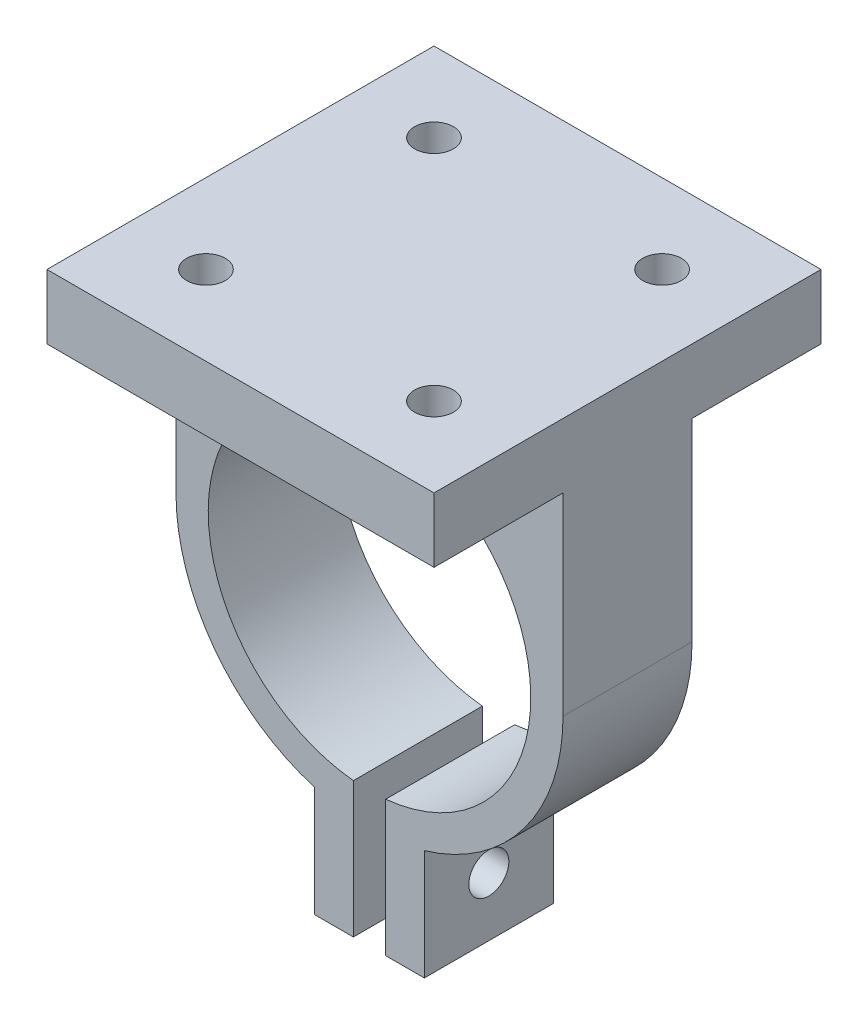
SolidWorks part; units mm, degrees
material "PLA"
ref_plane "Front Plane" through (0, 0, 0) normal (0, 0, 1) x (1, 0, 0)
ref_plane "Top Plane" through (0, 0, 0) normal (0, 1, 0) x (1, 0, 0)
ref_plane "Right Plane" through (0, 0, 0) normal (1, 0, 0) x (0, 0, -1)
sketch "Sketch1" plane through (0, 0, 0) normal (0, 0, 1) x (1, 0, 0)
  line L0 (-15, 0) -> (-15, 15)
  line L1 (-15, 15) -> (15, 15)
  line L2 (15, 15) -> (15, 0)
  line L4 (-1.25, -17.4373) -> (1.25, -17.4373)
  line L5 (-1.25, -17.4373) -> (-1.25, -12.4373)
  line L6 (-1.25, -12.4373) -> (1.25, -12.4373)
  line L7 (1.25, -17.4373) -> (1.25, -12.4373)
  line L8 (0, -44.7868) -> (0, 44.7868) construction
  circle A0 centre (0, 0) radius 12.5
  circle A1 centre (0, 0) radius 15
  dimension "D1" = 25
  dimension "D2" = 30
  dimension "D3" = 2.5
  dimension "D4" = 1.25
  dimension "D5" = 5
extrude "Boss-Extrude1" add sketch "Sketch1" along normal mid plane 10 contours A1 L1 L0 | A1 L2 L1 | A1 L5 A0 L7
sketch "Sketch2" plane through (0, 0, 0) normal (0, 0, 1) x (1, 0, 0)
  line L1 (-1.25, -12.4373) -> (-4.25, -12.4373)
  line L2 (-1.25, -12.4373) -> (-1.25, -22.9373)
  line L3 (-1.25, -22.9373) -> (-4.25, -22.9373)
  line L4 (-4.25, -12.4373) -> (-4.25, -22.9373)
  line L5 (1.25, -12.4373) -> (4.25, -12.4373)
  line L6 (1.25, -12.4373) -> (1.25, -22.9373)
  line L7 (1.25, -22.9373) -> (4.25, -22.9373)
  line L8 (4.25, -12.4373) -> (4.25, -22.9373)
  dimension "D1" = 3
  dimension "D2" = 10.5
extrude "Boss-Extrude2" add sketch "Sketch2" along normal mid plane 10
sketch "Sketch3" plane through (-4.25, 0, 0) normal (-1, 0, 0) x (0, 0, 1)
  line L0 (0, -44.2539) -> (0, 44.2539) construction
  line L3 (5, -14.3853) -> (-5, -14.3853) construction
  circle A0 centre (0, -18.3853) radius 1.55
  dimension "D1" = 3.1
  dimension "D2" = 4
extrude "Cut-Extrude1" cut sketch "Sketch3" against normal up to surface (8.5 mm away) up to face at (4.25, -18.6613, 0)
sketch "Sketch4" plane through (0, 15, 0) normal (0, 1, 0) x (1, 0, 0)
  line L0 (-15, -5) -> (-15, 5) construction
  line L1 (-15, 15) -> (15, 15)
  line L2 (-15, 15) -> (-15, -15)
  line L3 (-15, -15) -> (15, -15)
  line L4 (15, 15) -> (15, -15)
  line L5 (15, -5) -> (15, 5) construction
  line L6 (-44.2539, 0) -> (44.2539, 0) construction
  line L7 (0, -44.7868) -> (0, 44.7868) construction
  line L8 (-8.84, 8.84) -> (8.8377, 8.84)
  line L9 (-8.84, 8.84) -> (-8.84, -8.8377)
  line L10 (-8.84, -8.8377) -> (8.8377, -8.8377)
  line L11 (8.8377, 8.84) -> (8.8377, -8.8377)
  circle A0 centre (-8.84, 8.84) radius 1.5
  circle A1 centre (8.8377, 8.84) radius 1.5
  circle A2 centre (8.8377, -8.8377) radius 1.5
  circle A3 centre (-8.84, -8.8377) radius 1.5
  point P18 (0, 0)
  point P19 (0, 0)
  point P21 (-9.7432, 9.6975)
  line M5 (15, 5) -> (-15, 5)
  line M6 (-15, 5) -> (-15, -5)
  line M7 (-15, -5) -> (15, -5)
  line M8 (15, -5) -> (15, 5)
  dimension "D3" = 25
  dimension "D4" = 3
  dimension "D1" = 30
  dimension "D2" = 15
  dimension "D5" = 8.84
  dimension "D6" = 8.84
extrude "Boss-Extrude3" add sketch "Sketch4" along normal blind 5 contours A1 L11 L4 L1 L2 L9 A0 L8 M5 | L11 M5 M7 M8 | A3 L9 L2 L3 L4 L11 A2 L10 M7 | L9 M5 M6 M7 | A3 L10 A2 L11 L9 M7 | L11 L9 M5 M7 | A1 L8 A0 L9 L11 M5
sketch "Sketch5" plane through (0, 15, 0) normal (0, -1, 0) x (1, 0, 0)
  circle A0 centre (8.8377, 8.8377) radius 2.55
  dimension "D1" = 5.1
extrude "M3ScrewHead" [suppressed] add sketch "Sketch5" along normal blind 3.1
equation "\"InnerDiam\"=25"
equation "\"D1@Sketch1\"=\"InnerDiam\""
equation "\"OuterDiam\"=30"
equation "\"D2@Sketch1\"=\"OuterDiam\""
equation "\"TightenGap\"= 2.5"
equation "\"D3@Sketch1\"=\"TightenGap\""
equation "\"D4@Sketch1\"=\"TightenGap\"/2"
equation "\"D5@Sketch1\"=\"OuterDiam\"-\"InnerDiam\""
equation "\"ClampLen\"=10.5"
equation "\"D2@Sketch2\"=\"ClampLen\""
equation "\"Thick\"=10"
equation "\"D1@Boss-Extrude2\"=\"Thick\""
equation "\"D1@Boss-Extrude1\"=\"Thick\""
equation "\"D2@Sketch3\"=(\"ClampLen\"-2.5)/2"
equation "\"MotBaseThick\"=5"
equation "\"D1@Boss-Extrude3\"=\"MotBaseThick\""
